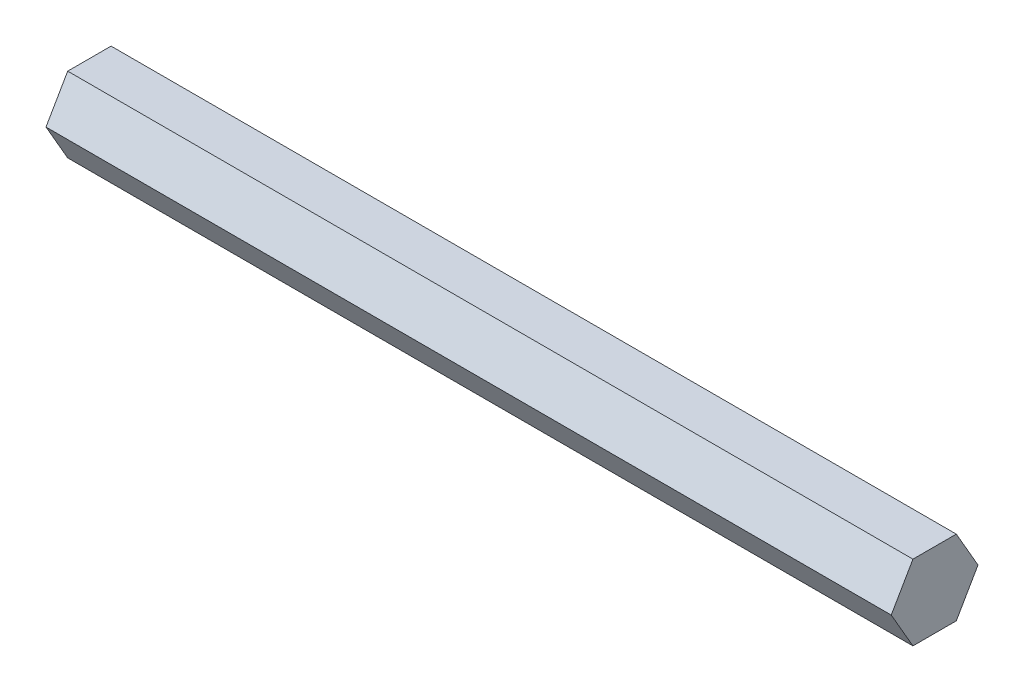
SolidWorks part; units mm, degrees
material "7075-T6 (SN)"
ref_plane "Front Plane" through (0, 0, 0) normal (0, 0, 1) x (1, 0, 0)
ref_plane "Top Plane" through (0, 0, 0) normal (0, 1, 0) x (1, 0, 0)
ref_plane "Right Plane" through (0, 0, 0) normal (1, 0, 0) x (0, 0, -1)
sketch "Sketch2" plane through (0, 0, 0) normal (1, 0, 0) x (0, 0, -1)
  line L1 (7.3323, 0) -> (3.6662, 6.35)
  line L2 (3.6662, 6.35) -> (-3.6662, 6.35)
  line L3 (-3.6662, 6.35) -> (-7.3323, 0)
  line L4 (-7.3323, 0) -> (-3.6662, -6.35)
  line L5 (-3.6662, -6.35) -> (3.6662, -6.35)
  line L6 (3.6662, -6.35) -> (7.3323, 0)
  circle A0 centre (0, 0) radius 6.35 construction
  dimension "D1" = 12.7
extrude "Boss-Extrude1" add sketch "Sketch2" along normal blind 142.875
